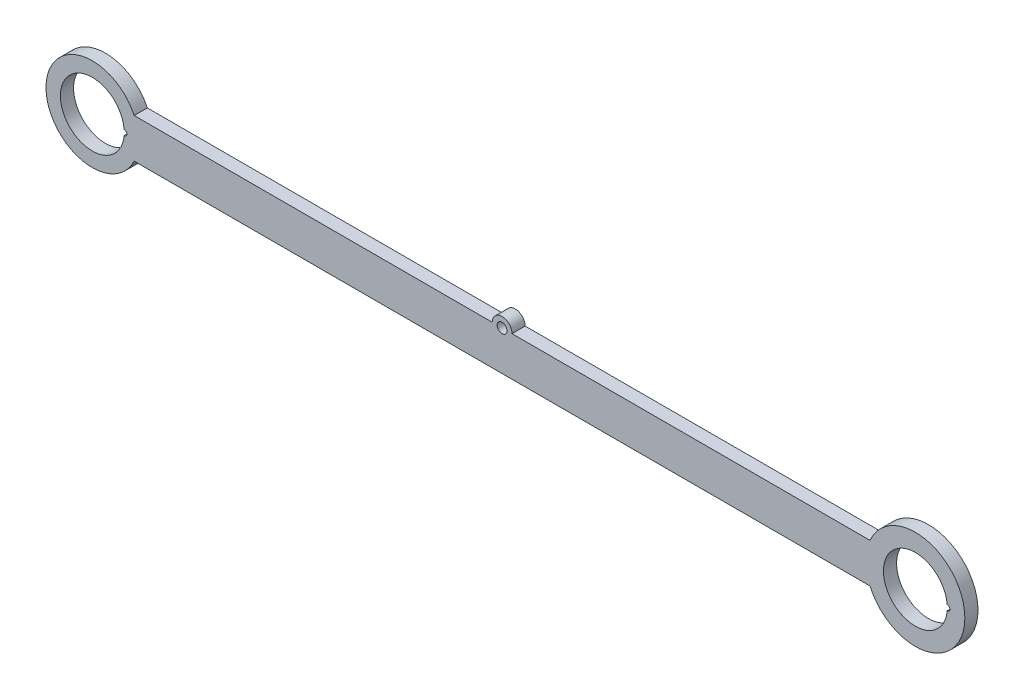
SolidWorks part; units mm, degrees
ref_plane "前视基准面" through (0, 0, 0) normal (0, 0, 1) x (1, 0, 0)
ref_plane "上视基准面" through (0, 0, 0) normal (0, 1, 0) x (1, 0, 0)
ref_plane "右视基准面" through (0, 0, 0) normal (1, 0, 0) x (0, 0, -1)
sketch "草图1" plane through (0, 0, 0) normal (0, 0, 1) x (1, 0, 0)
  line L0 (0, 0) -> (250, 0) construction
  line L1 (12.7187, 6) -> (236.2245, 6) construction
  line L2 (35.8014, 6) -> (35.8014, 0) construction
  line L3 (12.7187, -6) -> (236.2245, -6)
  line L4 (35.8014, 0) -> (35.8014, -6) construction
  line L5 (121.4716, 6) -> (12.7187, 6)
  line L6 (127.4716, 6) -> (236.2245, 6)
  circle A0 centre (0, 0) radius 9.7
  circle A1 centre (250, 0) radius 9.7
  circle A2 centre (0, 0) radius 14.0629 construction
  circle A3 centre (250, 0) radius 15.0255 construction
  arc A4 (12.7187, -6) -> (12.7187, 6) centre (0, 0) cw
  arc A5 (236.2245, -6) -> (236.2245, 6) centre (250, 0) ccw
  circle A6 centre (124.4716, 6) radius 1.5
  circle A7 centre (124.4716, 6) radius 3 construction
  arc A8 (121.4716, 6) -> (127.4716, 6) centre (124.4716, 6) cw
  dimension "D1" = 19.4
  dimension "D3" = 6
  dimension "D2" = 250
extrude "凸台-拉伸1" add sketch "草图1" along normal blind 4 contours L3 A5 L1 A4
sketch "草图3" plane through (0, 0, 4) normal (0, 0, 1) x (1, 0, 0)
  circle A0 centre (9.7, 0) radius 0.8
  circle A1 centre (0, 0) radius 9.7 construction
  circle A2 centre (259.7, 0) radius 0.8
  circle A3 centre (250, 0) radius 9.7 construction
extrude "切除-拉伸1" cut sketch "草图3" against normal blind 10
